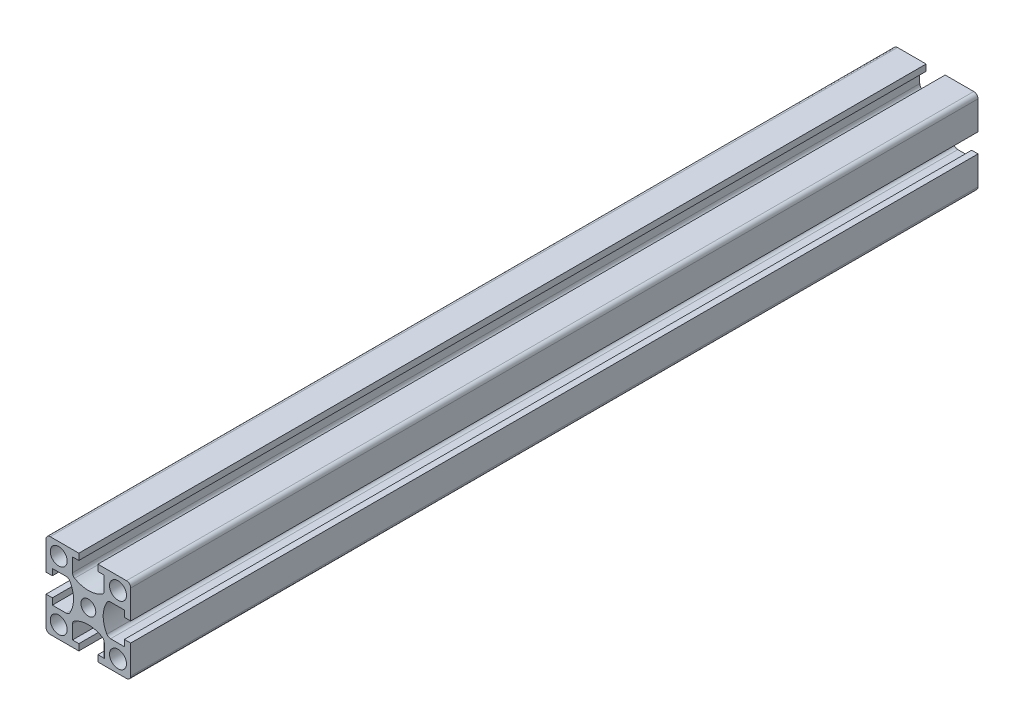
SolidWorks part; units mm, degrees
ref_plane "Front Plane" through (0, 0, 0) normal (0, 0, 1) x (1, 0, 0)
ref_plane "Top Plane" through (0, 0, 0) normal (0, 1, 0) x (1, 0, 0)
ref_plane "Right Plane" through (0, 0, 0) normal (1, 0, 0) x (0, 0, -1)
sketch "Sketch1" plane through (0, 0, 0) normal (0, 0, 1) x (1, 0, 0)
  line L64 (-25, 22.5) -> (-25, 5.625)
  line L65 (-25, 5.625) -> (-21.25, 5.625)
  line L66 (-21.25, 5.625) -> (-21.25, 9.375)
  line L67 (-21.25, 9.375) -> (-13.0922, 9.375)
  line L68 (-13.0922, -9.375) -> (-21.25, -9.375)
  line L69 (-21.25, -9.375) -> (-21.25, -5.625)
  line L70 (-21.25, -5.625) -> (-25, -5.625)
  line L71 (-25, -5.625) -> (-25, -22.5)
  line L72 (-22.5, -25) -> (-5.625, -25)
  line L73 (-5.625, -25) -> (-5.625, -21.25)
  line L74 (-5.625, -21.25) -> (-9.375, -21.25)
  line L75 (-9.375, -21.25) -> (-9.375, -13.0922)
  line L76 (9.375, -13.0922) -> (9.375, -21.25)
  line L77 (9.375, -21.25) -> (5.625, -21.25)
  line L78 (5.625, -21.25) -> (5.625, -25)
  line L79 (5.625, -25) -> (22.5, -25)
  line L80 (25, -22.5) -> (25, -5.625)
  line L81 (25, -5.625) -> (21.25, -5.625)
  line L82 (21.25, -5.625) -> (21.25, -9.375)
  line L83 (21.25, -9.375) -> (13.0922, -9.375)
  line L84 (13.0922, 9.375) -> (21.25, 9.375)
  line L85 (21.25, 9.375) -> (21.25, 5.625)
  line L86 (21.25, 5.625) -> (25, 5.625)
  line L87 (25, 5.625) -> (25, 22.5)
  line L88 (22.5, 25) -> (5.625, 25)
  line L89 (5.625, 25) -> (5.625, 21.25)
  line L90 (5.625, 21.25) -> (9.375, 21.25)
  line L91 (9.375, 21.25) -> (9.375, 13.0922)
  line L92 (-9.375, 13.0922) -> (-9.375, 21.25)
  line L93 (-9.375, 21.25) -> (-5.625, 21.25)
  line L94 (-5.625, 21.25) -> (-5.625, 25)
  line L95 (-5.625, 25) -> (-22.5, 25)
  circle A5 centre (-17.5, -17.5) radius 5
  circle A6 centre (17.5, -17.5) radius 5
  circle A7 centre (17.5, 17.5) radius 5
  circle A8 centre (0, 0) radius 4.375
  circle A9 centre (-17.5, 17.5) radius 5
  arc A32 (-22.5, 25) -> (-25, 22.5) centre (-22.5, 22.5) ccw
  arc A33 (-10.9271, 8.125) -> (-13.0922, 9.375) centre (-13.0922, 6.875) ccw
  arc A34 (-10.9271, -8.125) -> (-10.9271, 8.125) centre (-25, 0) ccw
  arc A35 (-13.0922, -9.375) -> (-10.9271, -8.125) centre (-13.0922, -6.875) ccw
  arc A36 (-25, -22.5) -> (-22.5, -25) centre (-22.5, -22.5) ccw
  arc A37 (-8.125, -10.9271) -> (-9.375, -13.0922) centre (-6.875, -13.0922) ccw
  arc A38 (8.125, -10.9271) -> (-8.125, -10.9271) centre (0, -25) ccw
  arc A39 (9.375, -13.0922) -> (8.125, -10.9271) centre (6.875, -13.0922) ccw
  arc A40 (22.5, -25) -> (25, -22.5) centre (22.5, -22.5) ccw
  arc A41 (10.9271, -8.125) -> (13.0922, -9.375) centre (13.0922, -6.875) ccw
  arc A42 (10.9271, 8.125) -> (10.9271, -8.125) centre (25, 0) ccw
  arc A43 (13.0922, 9.375) -> (10.9271, 8.125) centre (13.0922, 6.875) ccw
  arc A44 (25, 22.5) -> (22.5, 25) centre (22.5, 22.5) ccw
  arc A45 (8.125, 10.9271) -> (9.375, 13.0922) centre (6.875, 13.0922) ccw
  arc A46 (-8.125, 10.9271) -> (8.125, 10.9271) centre (0, 25) ccw
  arc A47 (-9.375, 13.0922) -> (-8.125, 10.9271) centre (-6.875, 13.0922) ccw
  dimension "D3" = 10
  dimension "D4" = 8.75
  dimension "D8" = 16.25
  dimension "D9" = 2.5
  dimension "D15" = 16.25
  dimension "D1" = 50
  dimension "D2" = 50
  dimension "D5" = 19.375
  dimension "D6" = 19.375
  dimension "D7" = 3.75
  dimension "D10" = 8.1578
  dimension "D11" = 3.75
  dimension "D12" = 8.1578
  dimension "D13" = 3.75
  dimension "D14" = 3.75
extrude "Boss-Extrude1" add sketch "Sketch1" along normal blind 500
